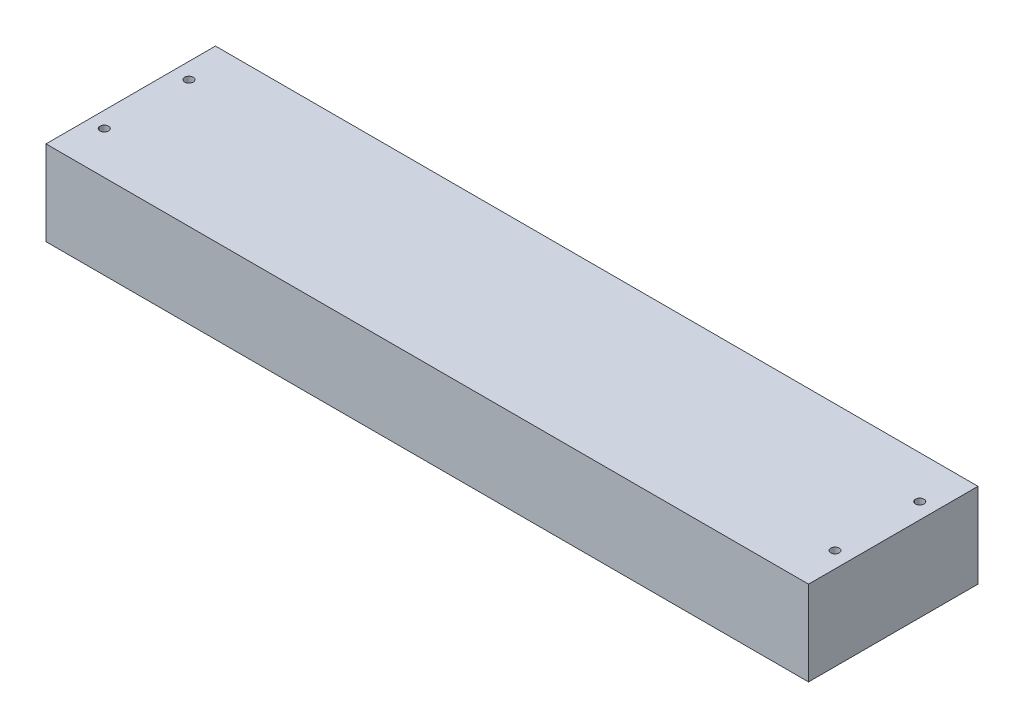
SolidWorks part; units mm, degrees
ref_plane "Front Plane" through (0, 0, 0) normal (0, 0, 1) x (1, 0, 0)
ref_plane "Top Plane" through (0, 0, 0) normal (0, 1, 0) x (1, 0, 0)
ref_plane "Right Plane" through (0, 0, 0) normal (1, 0, 0) x (0, 0, -1)
sketch "Sketch1" plane through (0, 0, 0) normal (1, 0, 0) x (0, 0, -1)
  line L1 (-50.8, 25.4) -> (50.8, 25.4)
  line L2 (-50.8, 25.4) -> (-50.8, -25.4)
  line L3 (-50.8, -25.4) -> (50.8, -25.4)
  line L4 (50.8, 25.4) -> (50.8, -25.4)
  line L5 (-50.8, 25.4) -> (50.8, -25.4) construction
  line L6 (-50.8, -25.4) -> (50.8, 25.4) construction
  point P0 (0, 0)
  dimension "D1" = 50.8
  dimension "D2" = 101.6
extrude "Boss-Extrude1" add sketch "Sketch1" along normal blind 457.2
ref_plane "Plane1" through (228.6, 0, 0) normal (-1, 0, 0) x (0, 0, 1)
sketch "Sketch3" plane through (0, 25.4, 0) normal (0, 1, 0) x (1, 0, 0)
  line L0 (457.2, -50.8) -> (0, -50.8) construction
  line L1 (0, 50.8) -> (0, -50.8) construction
  circle A0 centre (9.525, 25.4) radius 2.5527
  circle A1 centre (9.525, -25.4) radius 2.5527
  dimension "D3" = 5.1054
  dimension "D1" = 25.4
  dimension "D2" = 50.8
  dimension "D4" = 9.525
extrude "Cut-Extrude1" cut sketch "Sketch3" against normal up to surface (50.8 mm away) up to face at (228.6, -25.4, 0)
mirror "Mirror1" about plane through (228.6, 0, 0) normal (-1, 0, 0) of "Cut-Extrude1"
